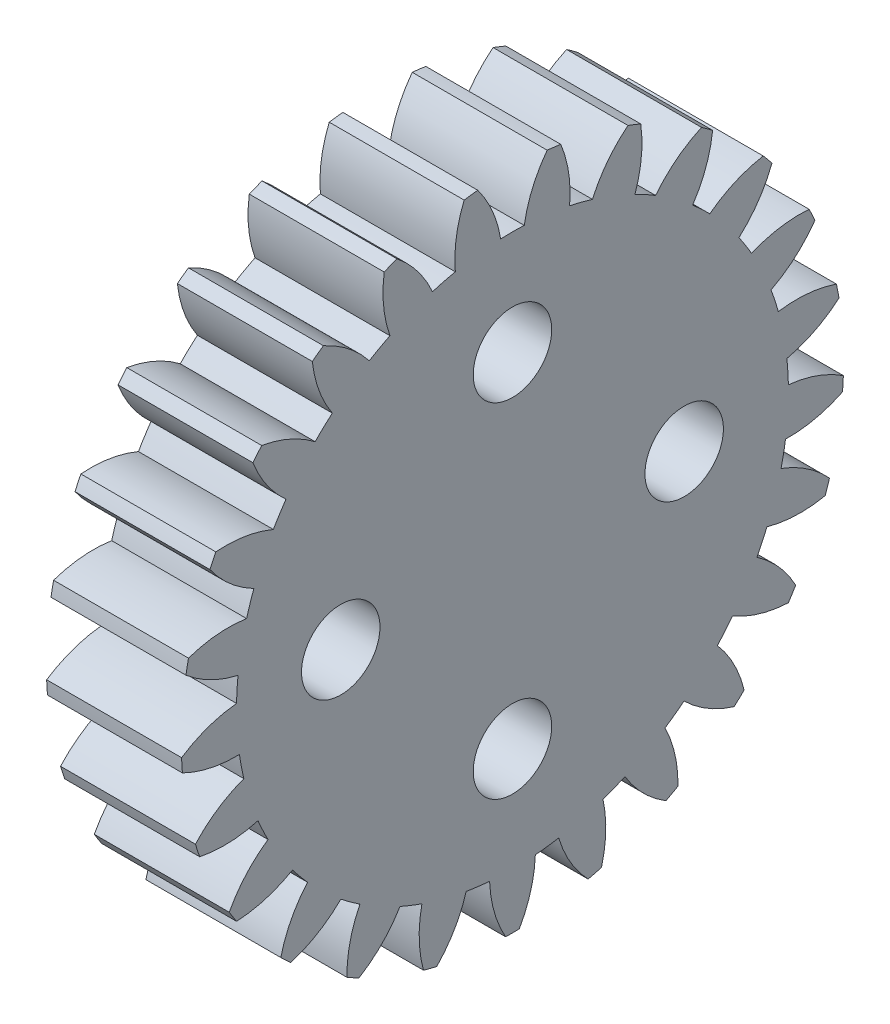
SolidWorks part; units mm, degrees
material "ﾎﾟﾘｵｷｼﾒﾁﾚﾝ(POM)ｱｾﾀｰﾙ共重合体"
ref_plane "Plane1" through (0, 0, 0) normal (0, 0, 1) x (1, 0, 0)
ref_plane "Plane2" through (0, 0, 0) normal (0, 1, 0) x (1, 0, 0)
ref_plane "Plane3" through (0, 0, 0) normal (1, 0, 0) x (0, 0, -1)
other "Configuration Table"
sketch "HoldingSke" plane through (0, 0, 0) normal (0, 1, 0) x (1, 0, 0)
  line L0 (0, 0) -> (0.9063, -0.4226)
  line L1 (-15, 0) -> (100, 0) construction
  line L2 (0, 0) -> (-2.1039, 2.3779)
  line L3 (0, 0) -> (-11.863, 4.5341)
  line L4 (0, 0) -> (7.8269, 3.6497)
  line L5 (0, 0) -> (-46.8476, -17.4728)
  line L6 (0, 0) -> (-4.5593, -3.0762)
  line L7 (-2.1039, 2.3779) -> (8.6586, 51.2059)
  line L8 (-76.2, 54.61) -> (-73.9, 54.61)
  line L9 (-71.009, 38.7566) -> (-53.1078, 45.2721)
  line L10 (-76.2, 71.12) -> (104.1128, 71.12)
  line L11 (0, 0) -> (-5.5, 0)
  line L12 (-76.2, 101.6) -> (-76.162, 101.6)
  line L13 (24.9733, 27.94) -> (52.9518, 28.4284)
  line L14 (24.9733, 27.94) -> (24.9743, 27.94)
  line L15 (24.9733, 27.94) -> (100.4006, 29.5858)
  line L16 (-63.627, -1) -> (-12.827, -1)
  circle A0 centre (0, 0) radius 7
  circle A1 centre (0, 0) radius 11.249
  circle A2 centre (0, 0) radius 37.5
  circle A3 centre (0, 0) radius 7
  dimension "MHD" = 22.498
  dimension "Hub_dia" = 75
  dimension "Bore" = 14
  dimension "MBD" = 14
  dimension "Num_teeth" = 25
  dimension "Pitch" = 1
  dimension "Overall_len" = 50
  dimension "Show_teeth" = 25
  dimension "Thickness" = 5.5
  dimension "OAL" = 50.0001
  dimension "T_dim" = 2.3
  dimension "Ap" = 20
  dimension "H" = 19.05
  dimension "Pitch_radius" = 180.3128
  dimension "Width" = 5.5
  dimension "Backlash" = 0.038
  dimension "Addendum_fac" = 1
  dimension "Dedendum_fac" = 1.25
  dimension "Clearance_fac" = 0.25
  dimension "Dedendum_add" = 0.001
  dimension "Module" = 1
sketch "BasProSke" plane through (0, 0, 0) normal (0, 1, 0) x (1, 0, 0)
  line L0 (-10, 0) -> (60, 0) construction
  line L1 (0, 0) -> (0, 13.5)
  line L2 (0, 0) -> (5.5, 0)
  line L3 (5.5, 0) -> (5.5, 13.5)
  line L4 (5.5, 13.5) -> (0, 13.5)
  dimension "Thickness" = 5.5
  dimension "Diameter" = 27
revolve "Base-Revolve" add sketch "BasProSke" angle 360 about L0
sketch "TooCutSke" plane through (0, 0, 0) normal (1, 0, 0) x (0, 0, -1)
  line L1 (0, 0) -> (0, 107) construction
  line L2 (0, 0) -> (-0.8514, 12.471) construction
  line L3 (0, 0) -> (-3.1282, 24.7619) construction
  line L4 (-0.8514, 12.471) -> (-1.5641, 12.3809) construction
  arc A0 (0.4801, 11.2388) -> (-0.4801, 11.2388) centre (0, 0) ccw
  arc A1 (1.4322, 13.4494) -> (-1.4322, 13.4494) centre (0, 0) ccw
  circle A2 centre (0, 0) radius 12.5 construction
  circle A3 centre (0, 0) radius 11.7462 construction
  arc A4 (-0.4801, 11.2388) -> (-1.4322, 13.4494) centre (-5.4133, 10.4244) ccw
  arc A5 (1.4322, 13.4494) -> (0.4801, 11.2388) centre (5.4133, 10.4244) ccw
  dimension "Root_dia" = 22.498
  dimension "Overcut_dia" = 27.0508
  dimension "Pitch_dia" = 25
  dimension "Base_dia" = 23.4923
  dimension "Flank_rad" = 5
  dimension "Half_ang" = 7.2
  dimension "Half_CT" = 0.7184
extrude "ToothCut" cut sketch "TooCutSke" along normal through all
fillet "Breaks" [suppressed] radius 0.02
fillet "RootFillets" [suppressed] radius 0.251
pattern_circular "TeethCuts" count 25 every 14.4 about axis through (-10, 0, 0) along (1, 0, 0) of "ToothCut", "RootFillets", "Breaks"
sketch "HubNeaOneSke" plane through (0, 0, 0) normal (-1, 0, 0) x (0, 0, 1)
  circle A0 centre (0, 0) radius 11.249
  dimension "Diameter" = 22.498
extrude "HubNearOne" [suppressed] add sketch "HubNeaOneSke" along normal blind 44.5001
sketch "HubNeaBotSke" plane through (0, 0, 0) normal (-1, 0, 0) x (0, 0, 1)
  circle A0 centre (0, 0) radius 11.249
  dimension "Diameter" = 22.498
extrude "HubNearBoth" [suppressed] add sketch "HubNeaBotSke" along normal blind 22.25
ref_plane "FarPln" through (5.5, 0, 0) normal (1, 0, 0) x (0, 0, -1)
sketch "HubFarSke" plane through (5.5, 0, 0) normal (1, 0, 0) x (0, 0, -1)
  circle A0 centre (0, 0) radius 11.249
  dimension "Diameter" = 22.498
extrude "HubFar" [suppressed] add sketch "HubFarSke" along normal blind 22.25
sketch "BorSke" plane through (0, 0, 0) normal (1, 0, 0) x (0, 0, -1)
  circle A0 centre (0, 0) radius 7
  dimension "Diameter" = 14
extrude "Bore" cut sketch "BorSke" along normal mid plane 100.0001
sketch "KeySke" plane through (0, 0, 0) normal (1, 0, 0) x (0, 0, -1)
  line L0 (-2.5, 0) -> (-2.5, 9.3)
  line L1 (-2.5, 9.3) -> (2.5, 9.3)
  line L2 (2.5, 9.3) -> (2.5, 0)
  line L3 (0, 0) -> (0, 34) construction
  line L4 (-2.5, 0) -> (2.5, 0)
  dimension "Offset" = 9.3
  dimension "Width" = 5
extrude "Keyway" [suppressed] cut sketch "KeySke" along normal mid plane 100.0001
pattern_circular "Keyway2" [suppressed] count 2 every 90 about axis through (-10, 0, 0) along (1, 0, 0)
sketch "ｽｹｯﾁ1" plane through (0, 0, 0) normal (-1, 0, 0) x (0, 0, 1)
  circle A0 centre (0, 0) radius 7
  circle A1 centre (0, 0) radius 7 construction
extrude "ﾎﾞｽ - 押し出し1" add sketch "ｽｹｯﾁ1" against normal up to surface (5.5 mm away) up to face at (5.5, 0, 7)
sketch "ｽｹｯﾁ2" plane through (5.5, 0, 0) normal (1, 0, 0) x (0, 0, -1)
  circle A0 centre (0, 0) radius 7 construction
  circle A1 centre (0, 7) radius 1.6
  circle A2 centre (7, 0) radius 1.6
  circle A3 centre (0, -7) radius 1.6
  circle A4 centre (-7, 0) radius 1.6
  point P14 (0, 0)
  dimension "D1" = 14
  dimension "D2" = 3.2
  dimension "D3" = 4
extrude "ｶｯﾄ - 押し出し1" cut sketch "ｽｹｯﾁ2" against normal through all
equation "' \"Module@HoldingSke\" = 6.35"
equation "' \"Num_teeth@HoldingSke\" = 12"
equation "' \"Ap@HoldingSke\" =  20"
equation "' \"Ap@HoldingSke\" = 20"
equation "' \"Width@HoldingSke\" = 0.5 * 25.4"
equation "' \"Hub_dia@HoldingSke\"= 1 * 25.4"
equation "' \"Hub_dia@HoldingSke\" = 1 * 25.4"
equation "' \"Overall_len@HoldingSke\" = 1.0 * 25.4"
equation "' \"Bore@HoldingSke\" = 0.75 * 25.4"
equation "' \"T_dim@HoldingSke\" = 0.1 * 25.4"
equation "' \"Width@KeySke\" = 0.25 * 25.4"
equation "' \"Show_teeth@HoldingSke\" = 13"
equation "' \"Backlash@HoldingSke\" = 0.009 * 25.4"
equation "' \"Addendum_fac@HoldingSke\" = 1.0"
equation "' \"Dedendum_fac@HoldingSke\" = 1.25"
equation "' \"Dedendum_add@HoldingSke\" = 0.00005 * 25.4"
equation "' \"Clearance_fac@HoldingSke\" = 0.25"
equation "\"Pitch@HoldingSke\" = 1 / \"Module@HoldingSke\""
equation "\"Overcut_dia@TooCutSke\" = (\"Num_teeth@HoldingSke\" + 2 * \"Addendum_fac@HoldingSke\") / \"Pitch@HoldingSke\" + 0.002 * 25.4"
equation "\"Pitch_dia@TooCutSke\" = \"Num_teeth@HoldingSke\" / \"Pitch@HoldingSke\""
equation "\"Base_dia@TooCutSke\" = \"Num_teeth@HoldingSke\" / \"Pitch@HoldingSke\" * cos((\"Ap@HoldingSke\"  * 3.14159265 / 180))"
equation "\"Root_dia@TooCutSke\" = (\"Num_teeth@HoldingSke\" + 2) / \"Pitch@HoldingSke\" - 2 * (\"Addendum_fac@HoldingSke\" + \"Dedendum_fac@HoldingSke\") / \"Pitch@HoldingSke\" - \"Dedendum_add@HoldingSke\" * 2"
equation "\"Half_ang@TooCutSke\" = 180 / \"Num_teeth@HoldingSke\""
equation "\"Half_CT@TooCutSke\" = \"Num_teeth@HoldingSke\" / \"Pitch@HoldingSke\" * sin((3.14159265 / 2 / \"Num_teeth@HoldingSke\")) / 2 - 7 * \"Backlash@HoldingSke\" / 4"
equation "\"Flank_rad@TooCutSke\" = \"Num_teeth@HoldingSke\" / \"Pitch@HoldingSke\" / 5"
equation "\"Radius@RootFillets\" = \"Clearance_fac@HoldingSke\" / \"Pitch@HoldingSke\" + \"Dedendum_add@HoldingSke\""
equation "\"Break_rad@Breaks\" = 0.02 / \"Pitch@HoldingSke\""
equation "\"Thickness@HoldingSke\" = \"Width@HoldingSke\""
equation "\"OAL@HoldingSke\" = \"Thickness@HoldingSke\""
equation "\"MHD@HoldingSke\" = (\"Num_teeth@HoldingSke\" + 2) / \"Pitch@HoldingSke\" - 2 * (\"Addendum_fac@HoldingSke\" + \"Dedendum_fac@HoldingSke\")  / \"Pitch@HoldingSke\" - \"Dedendum_add@HoldingSke\" * 2"
equation "\"MBD@HoldingSke\" = (\"Num_teeth@HoldingSke\" + 2) / \"Pitch@HoldingSke\" - 2 * (\"Addendum_fac@HoldingSke\" + \"Dedendum_fac@HoldingSke\")  / \"Pitch@HoldingSke\" - \"Dedendum_add@HoldingSke\" * 2 - 0.002 * 25.4"
equation "\"MHD@HoldingSke\" = ((sgn( \"MHD@HoldingSke\" - \"Hub_dia@HoldingSke\" )-1)*( \"MHD@HoldingSke\" - \"Hub_dia@HoldingSke\" ))/-2+ \"Hub_dia@HoldingSke\""
equation "\"MBD@HoldingSke\" = ((sgn( \"MBD@HoldingSke\" - \"Bore@HoldingSke\" )-1)*( \"MBD@HoldingSke\" - \"Bore@HoldingSke\" ))/-2+ \"Bore@HoldingSke\""
equation "\"OAL@HoldingSke\" = ((sgn( \"OAL@HoldingSke\" - \"Overall_len@HoldingSke\" )+1)*( \"OAL@HoldingSke\" - \"Overall_len@HoldingSke\" ))/2 + \"Overall_len@HoldingSke\" + 0.000002 * 25.4"
equation "\"Num_teeth@TeethCuts\" = int( \"Show_teeth@HoldingSke\" ) + 1"
equation "\"Num_teeth@TeethCuts\" = ((sgn( \"Num_teeth@TeethCuts\" - \"Num_teeth@HoldingSke\" )-1)*( \"Num_teeth@TeethCuts\" - \"Num_teeth@HoldingSke\" ))/-2+ \"Num_teeth@HoldingSke\""
equation "\"Num_teeth@TeethCuts\" = ((sgn( \"Num_teeth@TeethCuts\" - 2.0)+1)*( \"Num_teeth@TeethCuts\" - 2.0))/2 +2.0"
equation "\"Angle@TeethCuts\" = 360.0 / \"Num_teeth@HoldingSke\""
equation "\"Diameter@BasProSke\" = (\"Num_teeth@HoldingSke\" + 2 * \"Addendum_fac@HoldingSke\") / \"Pitch@HoldingSke\""
equation "\"Thickness@BasProSke\"  = \"Thickness@HoldingSke\""
equation "' \"Fillet_rad@BasProSke\" =  \"Thickness@HoldingSke\" * 0.05"
equation "' \"Fillet_rad@BasProSke\" = \"Thickness@HoldingSke\" * 0.05"
equation "\"MHD@HoldingSke\" = ((sgn( \"MHD@HoldingSke\" - \"Root_dia@TooCutSke\" )-1)*( \"MHD@HoldingSke\" - \"Root_dia@TooCutSke\" ))/-2+ \"Root_dia@TooCutSke\""
equation "\"Diameter@HubNeaOneSke\" = \"MHD@HoldingSke\""
equation "\"Length@HubNearOne\" = \"OAL@HoldingSke\" - \"Thickness@BasProSke\""
equation "\"Diameter@HubNeaBotSke\" = \"MHD@HoldingSke\""
equation "\"Length@HubNearBoth\" = ( \"OAL@HoldingSke\" - \"Thickness@BasProSke\" ) / 2.0"
equation "\"Thickness@FarPln\" = \"Thickness@BasProSke\""
equation "\"Diameter@HubFarSke\" = \"MHD@HoldingSke\""
equation "\"Length@HubFar\" = ( \"OAL@HoldingSke\" - \"Thickness@BasProSke\" ) / 2.0"
equation "\"Diameter@BorSke\" = \"MBD@HoldingSke\""
equation "\"D1@Bore\" = \"OAL@HoldingSke\" * 2.0"
equation "\"D1@Keyway\" = \"OAL@HoldingSke\" * 2.0"
equation "\"Offset@KeySke\" = \"T_dim@HoldingSke\" + \"MBD@HoldingSke\" / 2.0"
